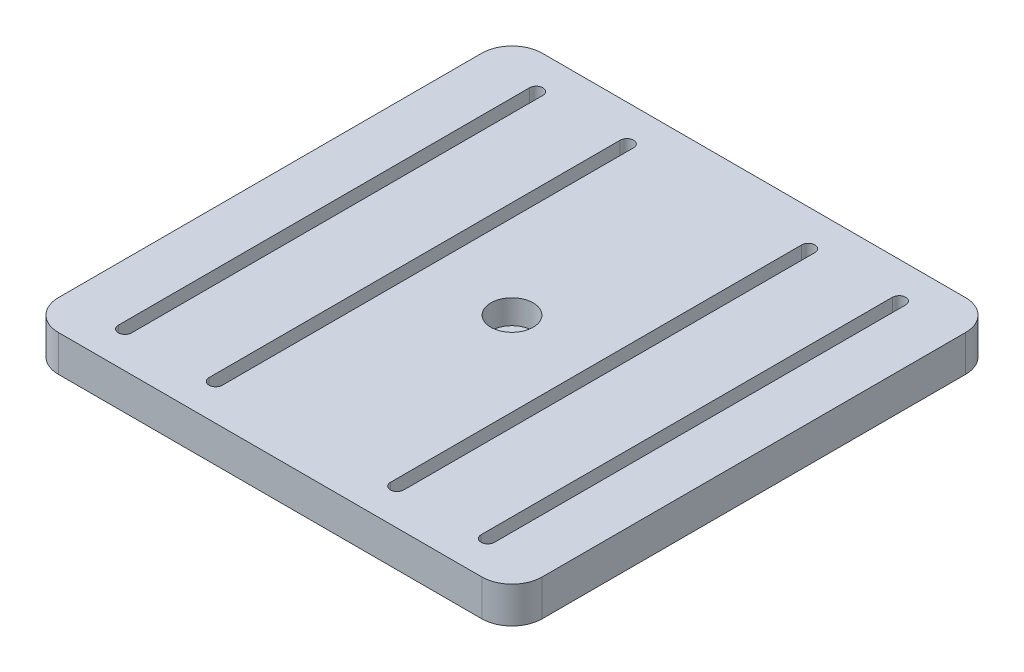
SolidWorks part; units mm, degrees
ref_plane "Front" through (0, 0, 0) normal (0, 0, 1) x (1, 0, 0)
ref_plane "Top" through (0, 0, 0) normal (0, 1, 0) x (1, 0, 0)
ref_plane "Right" through (0, 0, 0) normal (1, 0, 0) x (0, 0, -1)
sketch "Sketch1" plane through (0, 0, 0) normal (0, 1, 0) x (1, 0, 0)
  line L1 (-40, -40) -> (40, -40)
  line L2 (-40, -40) -> (-40, 40)
  line L3 (-40, 40) -> (40, 40)
  line L4 (40, -40) -> (40, 40)
  line L5 (-40, -40) -> (40, 40) construction
  line L6 (-40, 40) -> (40, -40) construction
  point P0 (0, 0)
  dimension "D1" = 80
  dimension "D2" = 80
extrude "Boss-Extrude1" add sketch "Sketch1" along normal blind 6
sketch "Sketch2" plane through (0, 6, 0) normal (0, 1, 0) x (1, 0, 0)
  line L1 (40, 40) -> (-40, 40) construction
  line L2 (15, 34) -> (15, -34) construction
  line L3 (16.1, 34) -> (16.1, -34)
  line L4 (13.9, 34) -> (13.9, -34)
  line L5 (0, 0) -> (15, 0) construction
  arc A0 (16.1, 34) -> (13.9, 34) centre (15, 34) ccw
  arc A1 (13.9, -34) -> (16.1, -34) centre (15, -34) ccw
  point P7 (15, 0)
  dimension "D2" = 2.2
  dimension "D1" = 15
  dimension "D3" = 6
extrude "Cut-Extrude1" cut sketch "Sketch2" against normal through all
sketch "Sketch4" plane through (0, 0, 0) normal (0, 1, 0) x (1, 0, 0)
  line L6 (13, 34) -> (13, -34)
  line L7 (17, -34) -> (17, 34)
  line L8 (13, 34) -> (13, -34)
  line L9 (17, -34) -> (17, 34)
  arc A5 (13, -34) -> (17, -34) centre (15, -34) ccw
  arc A6 (17, 34) -> (13, 34) centre (15, 34) ccw
  arc A7 (13, -34) -> (17, -34) centre (15, -34) ccw
  arc A8 (17, 34) -> (13, 34) centre (15, 34) ccw
  dimension "D1" = 0.9
extrude "Cut-Extrude2" cut sketch "Sketch4" along normal blind 1.8
pattern_linear "LPattern1" count 2 spacing 15 along (1, 0, 0) of "Cut-Extrude2", "Cut-Extrude1"
mirror "Mirror1" about plane through (0, 0, 0) normal (1, 0, 0) of "LPattern1", "Cut-Extrude1", "Cut-Extrude2"
sketch "Sketch5" plane through (0, 6, 0) normal (0, -1, 0) x (1, 0, 0)
  line L0 (0, -40) -> (0, 0) construction
  line L1 (40, -40) -> (-40, -40) construction
  circle A0 centre (0, 0) radius 3.5
  dimension "D2" = 7
extrude "Cut-Extrude3" cut sketch "Sketch5" along normal blind 4
sketch "Sketch6" plane through (0, 2, 0) normal (0, 1, 0) x (1, 0, 0)
  circle A0 centre (0, 0) radius 2.1
  dimension "D1" = 4.2
extrude "Cut-Extrude4" cut sketch "Sketch6" against normal through all
fillet "Fillet3" radius 5 4 edges at (-40, 3, 40) (-40, 3, -40) (40, 3, -40) (40, 3, 40)
